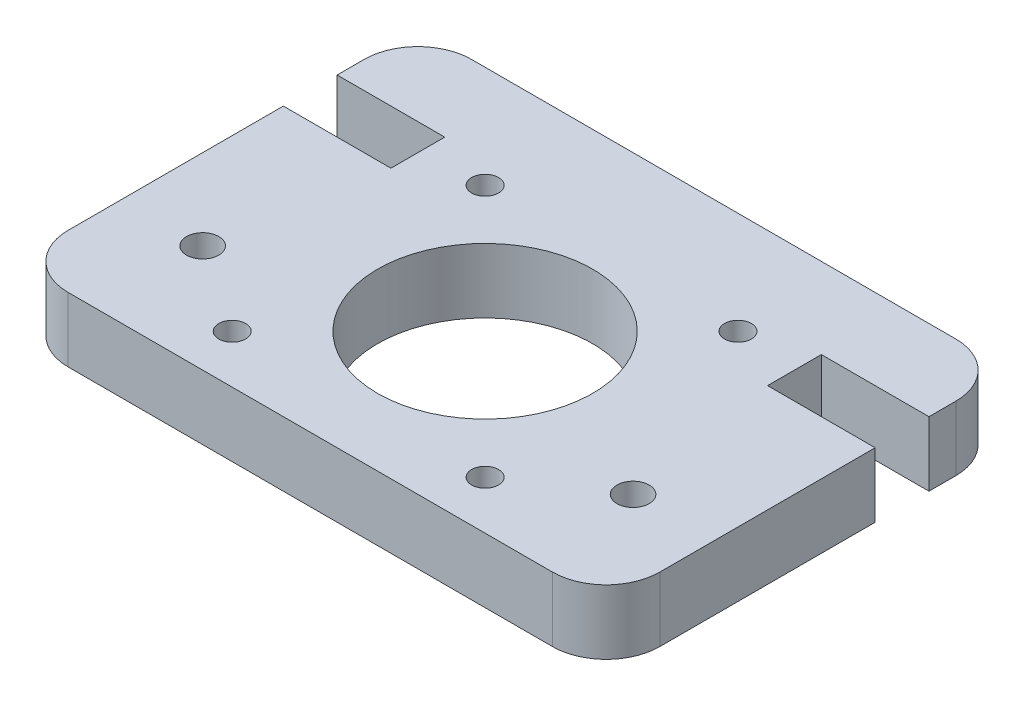
SolidWorks part; units mm, degrees
ref_plane "Front Plane" through (0, 0, 0) normal (0, 0, 1) x (1, 0, 0)
ref_plane "Top Plane" through (0, 0, 0) normal (0, 1, 0) x (1, 0, 0)
ref_plane "Right Plane" through (0, 0, 0) normal (1, 0, 0) x (0, 0, -1)
sketch "Sketch1" plane through (0, 0, 0) normal (0, 1, 0) x (1, 0, 0)
  line L0 (55, 50) -> (55, 15) construction
  line L1 (10, 0) -> (100, 0)
  line L2 (0, 10) -> (0, 50)
  line L3 (10, 75) -> (100, 75)
  line L4 (110, 10) -> (110, 50)
  line L5 (110, 50) -> (90, 50)
  line L6 (0, 50) -> (20, 50)
  line L7 (20, 50) -> (20, 60)
  line L8 (20, 60) -> (0, 60)
  line L9 (90, 50) -> (90, 60)
  line L10 (90, 60) -> (110, 60)
  line L11 (0, 60) -> (0, 65)
  line L12 (110, 60) -> (110, 65)
  line L13 (46.956, 32.5) -> (62.3253, 32.5) construction
  line L14 (78.5, 9) -> (31.5, 9) construction
  line L15 (78.5, 9) -> (78.5, 56) construction
  line L16 (78.5, 56) -> (31.5, 56) construction
  line L17 (31.5, 9) -> (31.5, 56) construction
  line L18 (78.5, 9) -> (31.5, 56) construction
  line L19 (78.5, 56) -> (31.5, 9) construction
  circle A5 centre (15, 20) radius 3
  arc A7 (100, 75) -> (110, 65) centre (100, 65) cw
  arc A8 (0, 65) -> (10, 75) centre (10, 65) cw
  arc A9 (100, 0) -> (110, 10) centre (100, 10) ccw
  arc A10 (10, 0) -> (0, 10) centre (10, 10) cw
  circle A11 centre (78.5, 56) radius 2.5
  circle A12 centre (95, 20) radius 3
  circle A13 centre (55, 32.5) radius 20
  circle A14 centre (31.5, 56) radius 2.5
  circle A15 centre (78.5, 9) radius 2.5
  circle A16 centre (31.5, 9) radius 2.5
  point P7 (55, 0)
  point P22 (55, 30)
  point P28 (0, 75)
  point P31 (110, 0)
  point P34 (0, 0)
  dimension "D4" = 47
  dimension "D6" = 32.5
  dimension "D10" = 6
  dimension "D13" = 10
  dimension "D3" = 40
  dimension "D7" = 5
  dimension "D1" = 75
  dimension "D2" = 110
  dimension "D5" = 47
  dimension "D11" = 20
  dimension "D12" = 15
  dimension "D14" = 50
  dimension "D15" = 10
  dimension "D16" = 20
extrude "Boss-Extrude1" add sketch "Sketch1" along normal blind 12
sketch "Sketch2" plane through (0, 0, 0) normal (0, -1, 0) x (1, 0, 0)
  line L1 (29.0463, -51.75) -> (26.5925, -56)
  line L2 (26.5925, -56) -> (29.0463, -60.25)
  line L3 (29.0463, -60.25) -> (33.9537, -60.25)
  line L4 (33.9537, -60.25) -> (36.4075, -56)
  line L5 (36.4075, -56) -> (33.9537, -51.75)
  line L6 (33.9537, -51.75) -> (29.0463, -51.75)
  line L7 (76.0463, -51.75) -> (73.5925, -56)
  line L8 (73.5925, -56) -> (76.0463, -60.25)
  line L9 (76.0463, -60.25) -> (80.9537, -60.25)
  line L10 (80.9537, -60.25) -> (83.4075, -56)
  line L11 (83.4075, -56) -> (80.9537, -51.75)
  line L12 (80.9537, -51.75) -> (76.0463, -51.75)
  circle A0 centre (31.5, -56) radius 4.25 construction
  circle A1 centre (78.5, -56) radius 4.25 construction
  dimension "D1" = 8.5
  dimension "D2" = 8.5
extrude "Cut-Extrude1" cut sketch "Sketch2" against normal blind 6
